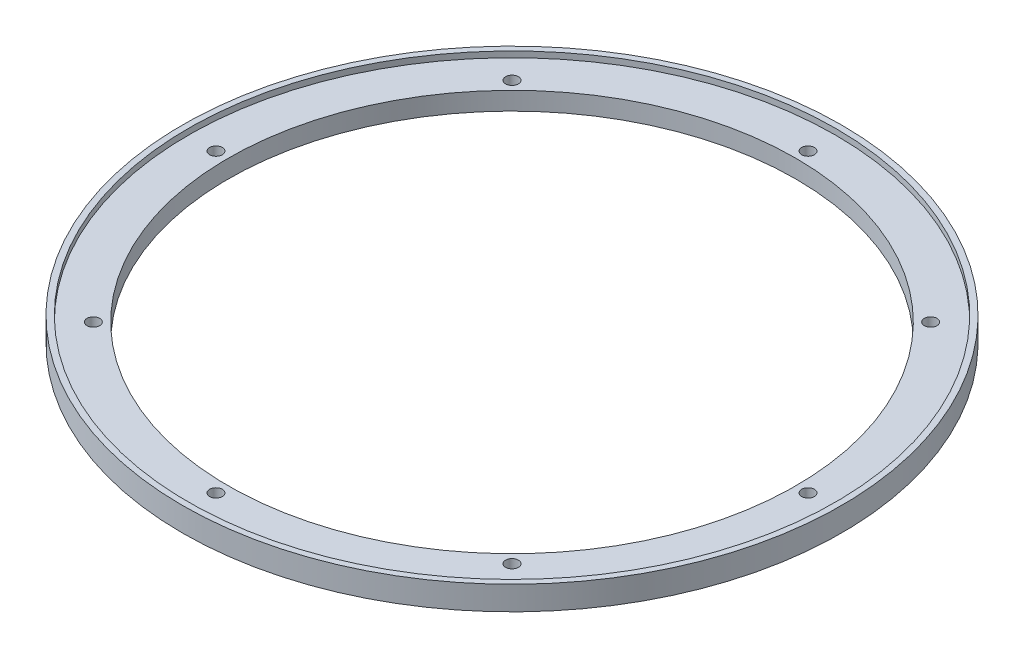
SolidWorks part; units mm, degrees
ref_plane "前视基准面" through (0, 0, 0) normal (0, 0, 1) x (1, 0, 0)
ref_plane "上视基准面" through (0, 0, 0) normal (0, 1, 0) x (1, 0, 0)
ref_plane "右视基准面" through (0, 0, 0) normal (1, 0, 0) x (0, 0, -1)
other "Configuration Table"
sketch "草图1" plane through (0, 0, 0) normal (0, 0, 1) x (1, 0, 0)
  line L0 (0, 0) -> (0, 17.2398) construction
  line L1 (111.6, 6.1) -> (111.6, 8.1)
  line L2 (96.1, 6.1) -> (109.6, 6.1)
  line L3 (96.1, 6.1) -> (96.1, 0)
  line L4 (96.1, 0) -> (111.6, 0)
  line L5 (111.6, 6.1) -> (111.6, 0)
  line L6 (111.6, 8.1) -> (109.6, 8.1)
  line L7 (109.6, 8.1) -> (109.6, 6.1)
  dimension "D1" = 6.1
  dimension "D2" = 13.5
  dimension "D3" = 96.1
  dimension "D4" = 2
  dimension "D5" = 2
revolve "旋转1" add sketch "草图1" angle 360 about L0
sketch "草图2" plane through (0, 6.1, 0) normal (0, 1, 0) x (1, 0, 0)
  circle A0 centre (0, 0) radius 100.25 construction
  circle A1 centre (-100.25, 0) radius 2.15
  circle A2 centre (-70.8875, 70.8875) radius 2.15
  circle A3 centre (0, 100.25) radius 2.15
  circle A4 centre (70.8875, 70.8875) radius 2.15
  circle A5 centre (100.25, 0) radius 2.15
  circle A6 centre (70.8875, -70.8875) radius 2.15
  circle A7 centre (0, -100.25) radius 2.15
  circle A8 centre (-70.8875, -70.8875) radius 2.15
  point P22 (0, 0)
  dimension "D1" = 200.5
  dimension "D2" = 4.3
  dimension "D3" = 8
extrude "切除-拉伸1" cut sketch "草图2" against normal up to next
sketch "草图3" plane through (0, 0, 0) normal (0, -1, 0) x (1, 0, 0)
  circle A1 centre (0, 0) radius 111.6
  circle A2 centre (0, 0) radius 111.6
  circle A3 centre (70.8875, 70.8875) radius 2.15
  circle A4 centre (70.8875, 70.8875) radius 2.15
  circle A5 centre (100.25, 0) radius 2.15
  circle A6 centre (100.25, 0) radius 2.15
  circle A7 centre (70.8875, -70.8875) radius 2.15
  circle A8 centre (70.8875, -70.8875) radius 2.15
  circle A9 centre (0, -100.25) radius 2.15
  circle A10 centre (0, -100.25) radius 2.15
  circle A11 centre (-70.8875, -70.8875) radius 2.15
  circle A12 centre (-70.8875, -70.8875) radius 2.15
  circle A13 centre (-100.25, 0) radius 2.15
  circle A14 centre (-100.25, 0) radius 2.15
  circle A15 centre (-70.8875, 70.8875) radius 2.15
  circle A16 centre (-70.8875, 70.8875) radius 2.15
  circle A17 centre (0, 100.25) radius 2.15
  circle A18 centre (0, 100.25) radius 2.15
  circle A19 centre (0, 0) radius 96.1
  circle A20 centre (0, 0) radius 96.1
  dimension "D1" = 0
  dimension "D2" = 0
  dimension "D3" = 0
  dimension "D4" = 0
  dimension "D5" = 0
  dimension "D6" = 0
  dimension "D7" = 0
  dimension "D8" = 0
  dimension "D9" = 0
  dimension "D10" = 0
extrude "凸台-拉伸1" [suppressed] add sketch "草图3" along normal blind 10
